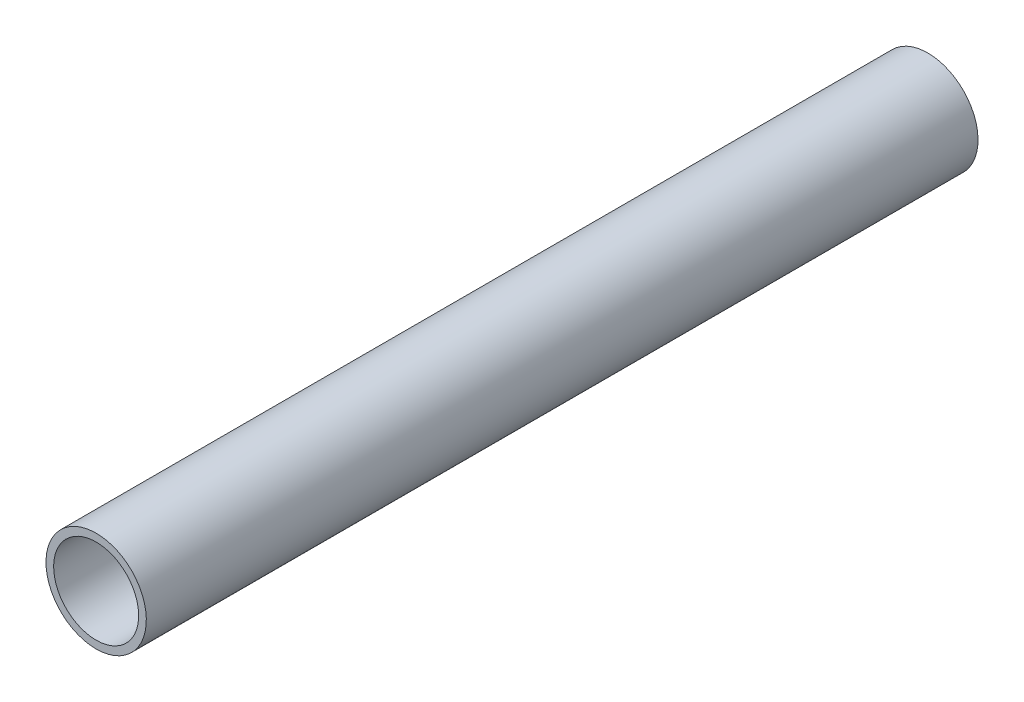
SolidWorks part; units mm, degrees
material "PVC Rígido"
ref_plane "Alzado" through (0, 0, 0) normal (0, 0, 1) x (1, 0, 0)
ref_plane "Planta" through (0, 0, 0) normal (0, 1, 0) x (1, 0, 0)
ref_plane "Vista lateral" through (0, 0, 0) normal (1, 0, 0) x (0, 0, -1)
sketch "Croquis2" plane through (0, 0, 0) normal (1, 0, 0) x (0, 0, -1)
  line L0 (-200, 0) -> (200, 0) construction
  line L1 (-200, 24.13) -> (-200, 20.447)
  line L2 (-200, 24.13) -> (200, 24.13)
  line L3 (200, 24.13) -> (200, 20.447)
  line L4 (200, 20.447) -> (50, 20.447)
  line L5 (-200, 20.447) -> (50, 20.447)
  point P3 (0, 0)
  dimension "D1" = 400
  dimension "D2" = 24.13
  dimension "D3" = 3.683
revolve "Revolución1" add sketch "Croquis2" angle 360 about L0
